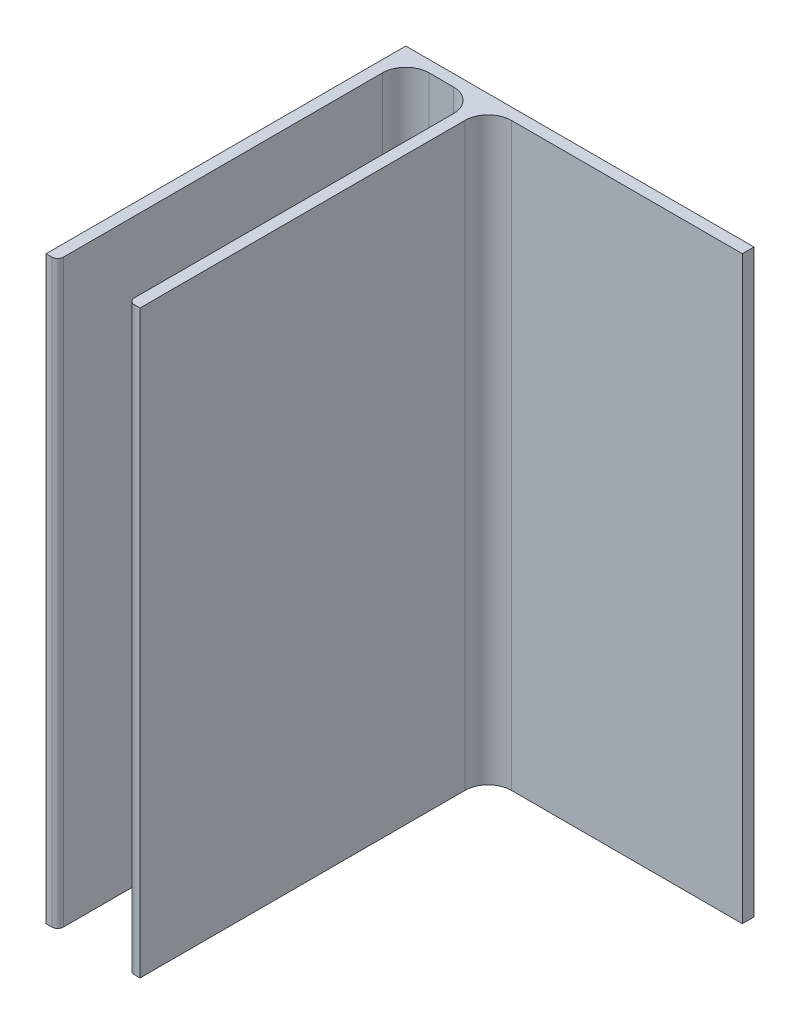
SolidWorks part; units mm, degrees
ref_plane "Front" through (0, 0, 0) normal (0, 0, 1) x (1, 0, 0)
ref_plane "Top" through (0, 0, 0) normal (0, 1, 0) x (1, 0, 0)
ref_plane "Right" through (0, 0, 0) normal (1, 0, 0) x (0, 0, -1)
sketch "Sketch1" plane through (0, 0, 0) normal (0, 0, 1) x (1, 0, 0)
  line L5 (0, 0) -> (30, 0)
  line L6 (0, 0) -> (0, 50)
  line L7 (0, 50) -> (30, 50)
  line L8 (30, 0) -> (30, 50)
  dimension "D1" = 50
  dimension "D2" = 30
extrude "Boss-Extrude1" add sketch "Sketch1" along normal blind 1
sketch "Sketch2" plane through (0, 0, 1) normal (0, 0, 1) x (1, 0, 0)
  line L0 (0, 0) -> (30, 0) construction
  line L1 (0, 50) -> (1, 50)
  line L2 (0, 50) -> (0, 0)
  line L3 (0, 0) -> (1, 0)
  line L4 (1, 50) -> (1, 0)
  line L10 (30, 50) -> (0, 50) construction
  line L11 (7.1, 50) -> (8.1, 50)
  line L12 (7.1, 50) -> (7.1, 0)
  line L13 (7.1, 0) -> (8.1, 0)
  line L14 (8.1, 50) -> (8.1, 0)
  dimension "D1" = 1
  dimension "D2" = 6.1
extrude "Boss-Extrude2" add sketch "Sketch2" along normal blind 30
fillet "Fillet2" radius 2 3 edges at (8.1, 25, 1) (1, 25, 1) (7.1, 25, 1)
fillet "Fillet3" radius 0.5 2 edges at (7.1, 25, 31) (1, 25, 31)
